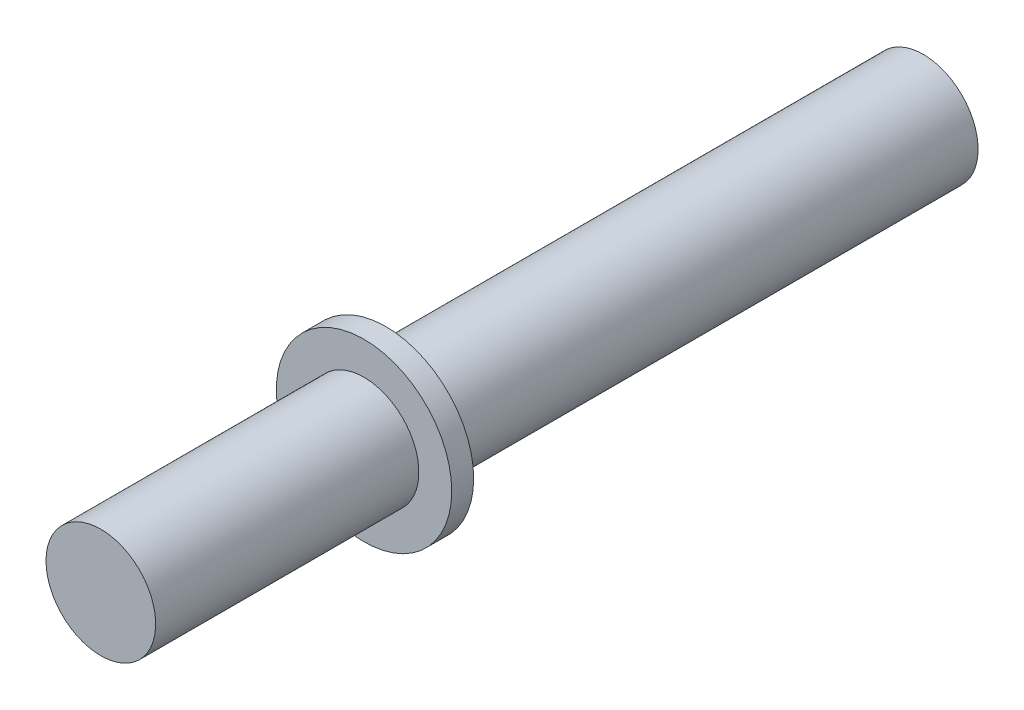
SolidWorks part; units mm, degrees
material "PVC Rigid"
ref_plane "Front Plane" through (0, 0, 0) normal (0, 0, 1) x (1, 0, 0)
ref_plane "Top Plane" through (0, 0, 0) normal (0, 1, 0) x (1, 0, 0)
ref_plane "Right Plane" through (0, 0, 0) normal (1, 0, 0) x (0, 0, -1)
sketch "Sketch1" plane through (0, 0, 0) normal (0, 0, 1) x (1, 0, 0)
  circle A0 centre (-32.0187, -41.7454) radius 1.5
extrude "Plunger_stem" add sketch "Sketch1" along normal blind 22.5 from offset 21.5
sketch "Sketch2" plane through (0, 0, 0) normal (0, 0, 1) x (1, 0, 0)
  circle A0 centre (-32.0187, -41.7454) radius 2.4
extrude "Captive_shoulder" add sketch "Sketch2" along normal blind 0.6 from offset 36.2
